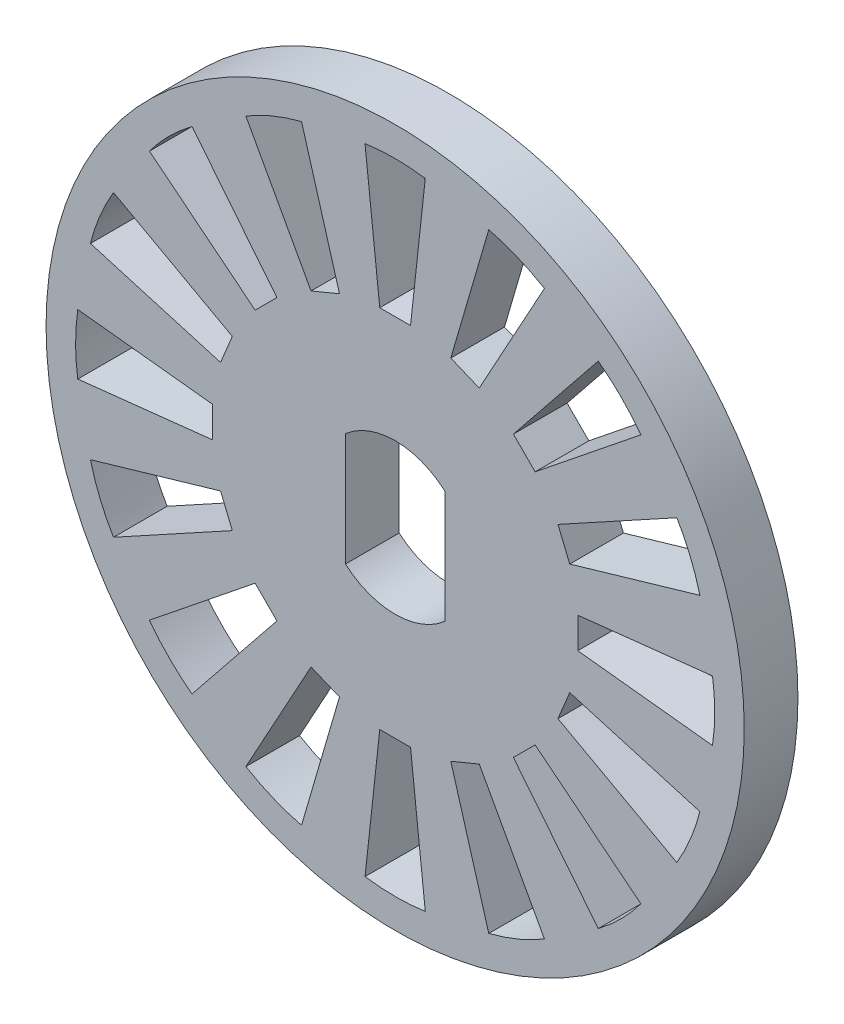
SolidWorks part; units mm, degrees
ref_plane "Front Plane" through (0, 0, 0) normal (0, 0, 1) x (1, 0, 0)
ref_plane "Top Plane" through (0, 0, 0) normal (0, 1, 0) x (1, 0, 0)
ref_plane "Right Plane" through (0, 0, 0) normal (1, 0, 0) x (0, 0, -1)
sketch "Sketch1" plane through (0, 0, 0) normal (0, 0, 1) x (1, 0, 0)
  line L0 (0, 29.3396) -> (0, -28.4316) construction
  line L1 (-34.5346, 0) -> (35.2675, 0) construction
  circle A0 centre (0, 0) radius 13
  dimension "D1" = 26
extrude "Boss-Extrude1" add sketch "Sketch1" along normal blind 2
sketch "Sketch2" plane through (0, 0, 2) normal (0, 0, 1) x (1, 0, 0)
  line L0 (0, 12.0457) -> (0, -12.3213) construction
  line L1 (-16.0712, 0) -> (16.7447, 0) construction
  line L2 (1.85, 2.1018) -> (1.85, -2.1018)
  line L3 (-1.85, 2.1018) -> (-1.85, -2.1018)
  arc A0 (-1.85, -2.1018) -> (1.85, -2.1018) centre (0, 0) ccw
  arc A1 (1.85, 2.1018) -> (-1.85, 2.1018) centre (0, 0) ccw
  point P11 (0, 0)
  dimension "D1" = 3.7
  dimension "D2" = 5.6
extrude "Cut-Extrude1" cut sketch "Sketch2" against normal blind 2
sketch "Sketch3" plane through (0, 0, 2) normal (0, 0, 1) x (1, 0, 0)
  line L0 (0, 13.934) -> (0, -12.3825) construction
  line L1 (-14.8773, 0) -> (14.2345, 0) construction
  line L2 (-0.5733, 6.8) -> (0.5733, 6.8)
  line L3 (0.5733, 6.8) -> (1.1218, 11.8185)
  line L4 (-0.5733, 6.8) -> (-1.1218, 11.8185)
  line L6 (3.1319, 6.063) -> (5.5591, 10.4896)
  line L7 (2.0726, 6.5018) -> (3.1319, 6.063)
  line L8 (2.0726, 6.5018) -> (3.4864, 11.3481)
  line L9 (5.2137, 4.403) -> (9.1501, 7.5637)
  line L10 (4.403, 5.2137) -> (5.2137, 4.403)
  line L11 (4.403, 5.2137) -> (7.5637, 9.1501)
  line L12 (6.5018, 2.0726) -> (11.3481, 3.4864)
  line L13 (6.063, 3.1319) -> (6.5018, 2.0726)
  line L14 (6.063, 3.1319) -> (10.4896, 5.5591)
  line L15 (6.8, -0.5733) -> (11.8185, -1.1218)
  line L16 (6.8, 0.5733) -> (6.8, -0.5733)
  line L17 (6.8, 0.5733) -> (11.8185, 1.1218)
  line L18 (6.063, -3.1319) -> (10.4896, -5.5591)
  line L19 (6.5018, -2.0726) -> (6.063, -3.1319)
  line L20 (6.5018, -2.0726) -> (11.3481, -3.4864)
  line L21 (4.403, -5.2137) -> (7.5637, -9.1501)
  line L22 (5.2137, -4.403) -> (4.403, -5.2137)
  line L23 (5.2137, -4.403) -> (9.1501, -7.5637)
  line L24 (2.0726, -6.5018) -> (3.4864, -11.3481)
  line L25 (3.1319, -6.063) -> (2.0726, -6.5018)
  line L26 (3.1319, -6.063) -> (5.5591, -10.4896)
  line L27 (-0.5733, -6.8) -> (-1.1218, -11.8185)
  line L28 (0.5733, -6.8) -> (-0.5733, -6.8)
  line L29 (0.5733, -6.8) -> (1.1218, -11.8185)
  line L30 (-3.1319, -6.063) -> (-5.5591, -10.4896)
  line L31 (-2.0726, -6.5018) -> (-3.1319, -6.063)
  line L32 (-2.0726, -6.5018) -> (-3.4864, -11.3481)
  line L33 (-5.2137, -4.403) -> (-9.1501, -7.5637)
  line L34 (-4.403, -5.2137) -> (-5.2137, -4.403)
  line L35 (-4.403, -5.2137) -> (-7.5637, -9.1501)
  line L36 (-6.5018, -2.0726) -> (-11.3481, -3.4864)
  line L37 (-6.063, -3.1319) -> (-6.5018, -2.0726)
  line L38 (-6.063, -3.1319) -> (-10.4896, -5.5591)
  line L39 (-6.8, 0.5733) -> (-11.8185, 1.1218)
  line L40 (-6.8, -0.5733) -> (-6.8, 0.5733)
  line L41 (-6.8, -0.5733) -> (-11.8185, -1.1218)
  line L42 (-6.063, 3.1319) -> (-10.4896, 5.5591)
  line L43 (-6.5018, 2.0726) -> (-6.063, 3.1319)
  line L44 (-6.5018, 2.0726) -> (-11.3481, 3.4864)
  line L45 (-4.403, 5.2137) -> (-7.5637, 9.1501)
  line L46 (-5.2137, 4.403) -> (-4.403, 5.2137)
  line L47 (-5.2137, 4.403) -> (-9.1501, 7.5637)
  line L48 (-2.0726, 6.5018) -> (-3.4864, 11.3481)
  line L49 (-3.1319, 6.063) -> (-2.0726, 6.5018)
  line L50 (-3.1319, 6.063) -> (-5.5591, 10.4896)
  arc A2 (1.85, 2.1018) -> (-1.85, 2.1018) centre (0, 0) ccw construction
  spline S0 degree 2 poles (-1.1218, 11.8185) (0, 11.9816) (1.1218, 11.8185) knots 0 0 0 1 1 1
  spline S1 degree 2 poles (3.4864, 11.3481) (4.5852, 11.0695) (5.5591, 10.4896) knots 0 0 0 1 1 1
  spline S2 degree 2 poles (7.5637, 9.1501) (8.4723, 8.4723) (9.1501, 7.5637) knots 0 0 0 1 1 1
  spline S3 degree 2 poles (10.4896, 5.5591) (11.0695, 4.5852) (11.3481, 3.4864) knots 0 0 0 1 1 1
  spline S4 degree 2 poles (11.8185, 1.1218) (11.9816, 0) (11.8185, -1.1218) knots 0 0 0 1 1 1
  spline S5 degree 2 poles (11.3481, -3.4864) (11.0695, -4.5852) (10.4896, -5.5591) knots 0 0 0 1 1 1
  spline S6 degree 2 poles (9.1501, -7.5637) (8.4723, -8.4723) (7.5637, -9.1501) knots 0 0 0 1 1 1
  spline S7 degree 2 poles (5.5591, -10.4896) (4.5852, -11.0695) (3.4864, -11.3481) knots 0 0 0 1 1 1
  spline S8 degree 2 poles (1.1218, -11.8185) (0, -11.9816) (-1.1218, -11.8185) knots 0 0 0 1 1 1
  spline S9 degree 2 poles (-3.4864, -11.3481) (-4.5852, -11.0695) (-5.5591, -10.4896) knots 0 0 0 1 1 1
  spline S10 degree 2 poles (-7.5637, -9.1501) (-8.4723, -8.4723) (-9.1501, -7.5637) knots 0 0 0 1 1 1
  spline S11 degree 2 poles (-10.4896, -5.5591) (-11.0695, -4.5852) (-11.3481, -3.4864) knots 0 0 0 1 1 1
  spline S12 degree 2 poles (-11.8185, -1.1218) (-11.9816, 0) (-11.8185, 1.1218) knots 0 0 0 1 1 1
  spline S13 degree 2 poles (-11.3481, 3.4864) (-11.0695, 4.5852) (-10.4896, 5.5591) knots 0 0 0 1 1 1
  spline S14 degree 2 poles (-9.1501, 7.5637) (-8.4723, 8.4723) (-7.5637, 9.1501) knots 0 0 0 1 1 1
  spline S15 degree 2 poles (-5.5591, 10.4896) (-4.5852, 11.0695) (-3.4864, 11.3481) knots 0 0 0 1 1 1
  point P10 (0.5733, 6.8)
  point P91 (0, 0)
  point P121 (0, 0)
  point P122 (0, 0)
  point P137 (0, 0)
  dimension "D2" = 4
  dimension "D1" = 16
extrude "Cut-Extrude2" cut sketch "Sketch3" against normal blind 2
